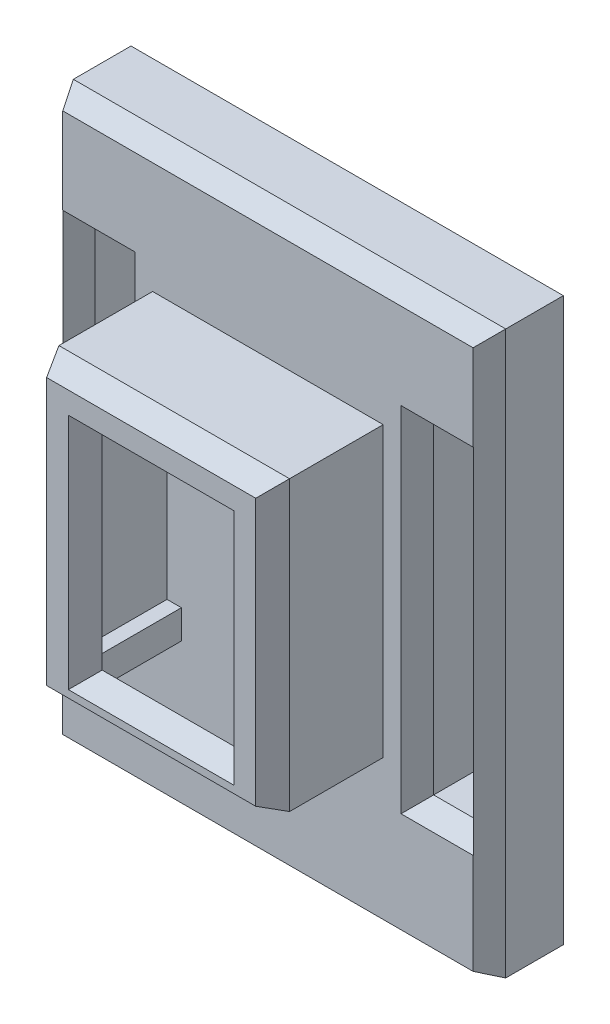
SolidWorks part; units mm, degrees
ref_plane "Plano frontal" through (0, 0, 0) normal (0, 0, 1) x (1, 0, 0)
ref_plane "Plano superior" through (0, 0, 0) normal (0, 1, 0) x (1, 0, 0)
ref_plane "Plano direito" through (0, 0, 0) normal (1, 0, 0) x (0, 0, -1)
sketch "Esboço1" plane through (0, 0, 0) normal (0, 0, 1) x (1, 0, 0)
  line L0 (0, 0) -> (10, 0)
  line L1 (0, 0) -> (-10, 0)
  line L2 (0, 0) -> (0, 24)
  line L3 (0, 24) -> (12.5, 24)
  line L4 (12.5, 24) -> (12.5, 0)
  line L5 (0, 24) -> (-12.5, 24)
  line L6 (-12.5, 24) -> (-12.5, 0)
  line L7 (-12.5, 0) -> (-12.5, -10)
  line L8 (-12.5, -10) -> (12.5, -10)
  line L9 (12.5, -10) -> (12.5, 0)
  line L10 (10, 19) -> (10, -4)
  line L11 (-10, 19) -> (-10, -4)
  line L12 (-7.5, 24) -> (-7.5, 0)
  line L13 (7.5, 24) -> (7.5, 0)
  line L14 (0, 19) -> (-7.5, 19)
  line L15 (0, 19) -> (7.5, 19)
  line L16 (0, -4) -> (13.5, -4)
  line L17 (0, -4) -> (-13.5, -4)
  line L18 (-10, 24) -> (-10, 0) construction
  line L19 (10, 24) -> (10, 0) construction
  line L20 (10, 19) -> (13.5, 19)
  line L21 (-10, 19) -> (-13.5, 19)
  line L22 (0, 19) -> (12.5, 19) construction
  line L23 (0, 25) -> (-13.5, 25)
  line L24 (0, 19) -> (-12.5, 19) construction
  line L25 (-13.5, 25) -> (-13.5, 0)
  line L26 (-13.5, 0) -> (-13.5, -11)
  line L27 (-13.5, -11) -> (13.5, -11)
  line L28 (13.5, -11) -> (13.5, 0)
  line L29 (13.5, 25) -> (13.5, 0)
  line L30 (0, 25) -> (13.5, 25)
  line L31 (0, 0) -> (-12.5, 0) construction
  line L32 (0, 0) -> (12.5, 0) construction
  line L33 (0, -4) -> (12.5, -4) construction
  line L34 (0, -4) -> (-12.5, -4) construction
  line L35 (0, 26.5) -> (-15, 26.5)
  line L36 (-15, 26.5) -> (-15, 0)
  line L37 (-15, 0) -> (-15, -12.5)
  line L38 (-15, -12.5) -> (15, -12.5)
  line L39 (15, -12.5) -> (15, 0)
  line L40 (15, 26.5) -> (15, 0)
  line L41 (0, 26.5) -> (15, 26.5)
  line L42 (0, -12.5) -> (0, -4)
  line L43 (6, -12.5) -> (6, -4)
  line L44 (-6, -12.5) -> (-6, -4)
extrude "Ressalto-extrusão1" add sketch "Esboço1" along normal blind 4 contours L38 L44 L27 L26 L25 L23 L30 L29 L28 L43 L39 L40 L41 L35 L36 L37 | L21 L11 L1 L12 L5 L6 | L10 L20 L4 L3 L13 L0 | L17 L16 L10 L0 L1 L11 | L8 L44 L17 L7 | L27 L44 L8 L7 L17 L26 | L43 L8 L9 L16 | L43 L27 L28 L16 L9 L8 | L44 L8 L42 L17 | L8 L43 L16 L42 | L27 L43 L8 L42 | L44 L27 L42 L8 | L44 L38 L42 L27 | L38 L43 L27 L42
sketch "Esboço2" plane through (0, 0, 4) normal (0, 0, 1) x (1, 0, 0)
  line L1 (-15, 26.5) -> (15, 26.5)
  line L2 (-15, 26.5) -> (-15, -12.5)
  line L3 (-15, -12.5) -> (15, -12.5)
  line L4 (15, 26.5) -> (15, -12.5)
  line L5 (10, 19) -> (13.5, 19)
  line L6 (10, 19) -> (10, -4)
  line L7 (10, -4) -> (13.5, -4)
  line L8 (13.5, 19) -> (13.5, -4)
  line L9 (-10, 19) -> (-13.5, 19)
  line L10 (-10, 19) -> (-10, -4)
  line L11 (-10, -4) -> (-13.5, -4)
  line L12 (-13.5, 19) -> (-13.5, -4)
extrude "Ressalto-extrusão2" add sketch "Esboço2" along normal blind 1.5 draft 27
sketch "Esboço3" plane through (0, 0, 5.5) normal (0, 0, 1) x (1, 0, 0)
  line L0 (-9.2357, 19.7643) -> (9.2357, 19.7643)
  line L1 (9.2357, 19.7643) -> (9.2357, -4.7643)
  line L2 (9.2357, -4.7643) -> (-9.2357, -4.7643)
  line L3 (-9.2357, -4.7643) -> (-9.2357, 19.7643)
  line L4 (0, 0) -> (0, 16)
  line L5 (-7, 16) -> (7, 16)
  line L6 (6, 17) -> (6, -2)
  line L7 (7, 0) -> (-7, 0)
  line L8 (-6, 17) -> (-6, -2)
  line L9 (-7, 17) -> (7, 17)
  line L10 (7, 17) -> (7, -2)
  line L11 (7, -1) -> (-7, -1)
  line L12 (-7, 17) -> (-7, -2)
  line L13 (-8, 18) -> (8, 18)
  line L14 (8, 18) -> (8, -2)
  line L15 (8, -2) -> (-8, -2)
  line L16 (-8, 18) -> (-8, -2)
  line L17 (-8.2357, -3.7643) -> (-8.2357, 18.7643)
  line L18 (-8.2357, 18.7643) -> (8.2357, 18.7643)
  line L19 (8.2357, 18.7643) -> (8.2357, -3.7643)
  line L20 (8.2357, -3.7643) -> (-8.2357, -3.7643)
  line L21 (5, 15) -> (5, 0)
  line L22 (-5, 15) -> (5, 15)
  line L23 (-5, 15) -> (-5, 0)
  line L24 (-7, 17) -> (-7, -1) construction
  line L25 (7, 17) -> (7, -1) construction
  line L26 (6, 16) -> (6, 0) construction
  line L27 (-6, 16) -> (-6, 0) construction
  line L28 (6, 0) -> (-6, 0) construction
  line L29 (-6, 16) -> (6, 16) construction
extrude "Ressalto-extrusão3" add sketch "Esboço3" along normal blind 6.5 contours L13 L16 L15 L12 L9 L10 L14 | L15 L8 L11 L12 | L7 L12 L11 L8 | L9 L12 L5 L8 | L10 L9 L6 L5 | L11 L10 L7 L6 | L15 L10 L11 L6
sketch "Esboço4" plane through (0, 0, 12) normal (0, 0, 1) x (1, 0, 0)
  line L1 (-8, 18) -> (8, 18)
  line L2 (-8, 18) -> (-8, -2)
  line L3 (-8, -2) -> (8, -2)
  line L4 (8, 18) -> (8, -2)
  line L5 (-5, 15) -> (5, 15)
  line L6 (-5, 15) -> (-5, 0)
  line L7 (-5, 0) -> (5, 0)
  line L8 (5, 15) -> (5, 0)
extrude "Ressalto-extrusão4" add sketch "Esboço4" along normal blind 1.6 draft 25
